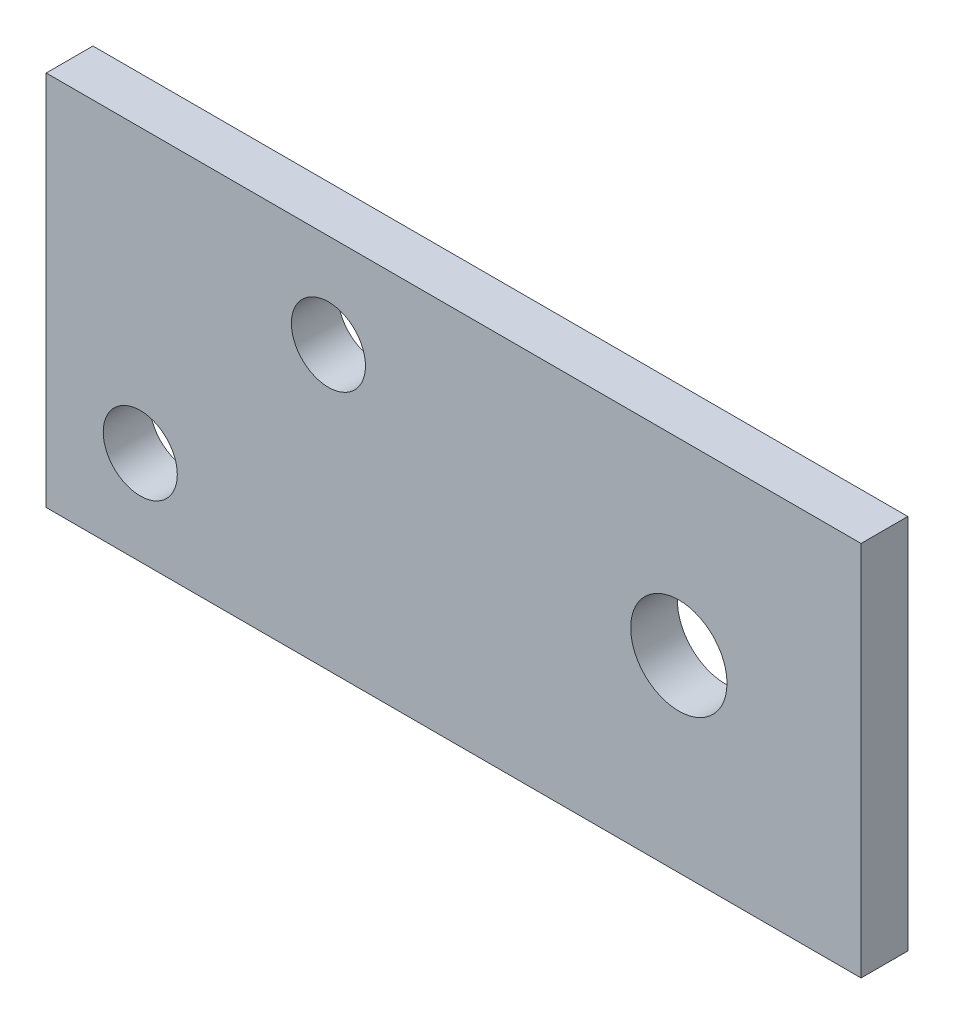
SolidWorks part; units mm, degrees
ref_plane "Alzado" through (0, 0, 0) normal (0, 0, 1) x (1, 0, 0)
ref_plane "Planta" through (0, 0, 0) normal (0, 1, 0) x (1, 0, 0)
ref_plane "Vista lateral" through (0, 0, 0) normal (1, 0, 0) x (0, 0, -1)
sketch "Croquis1" plane through (0, 0, 0) normal (0, 0, 1) x (1, 0, 0)
  line L0 (-59.2, 50.8) -> (-110, 50.8)
  line L1 (-110, 50.8) -> (-110, 0)
  line L2 (-110, 0) -> (0, 0)
  line L3 (0, 0) -> (0, 50.8)
  line L4 (0, 50.8) -> (-59.2, 50.8)
  circle A0 centre (-24.6, 25.4013) radius 6.5013
  point P7 (0, 0)
  point P8 (0, 0)
  dimension "D3" = 13.0027
  dimension "D1" = 110
  dimension "D2" = 50.8
  dimension "D4" = 25.4013
  dimension "D5" = 24.6
  dimension "D6" = 50.8
extrude "Saliente-Extruir1" add sketch "Croquis1" along normal blind 6.31
sketch "Croquis2" plane through (0, 0, 0) normal (0, 0, -1) x (-1, 0, 0)
  circle A0 centre (97.3, 12.7) radius 5
  circle A1 centre (71.9, 38.1) radius 5
extrude "Cortar-Extruir1" cut sketch "Croquis2" against normal blind 10
